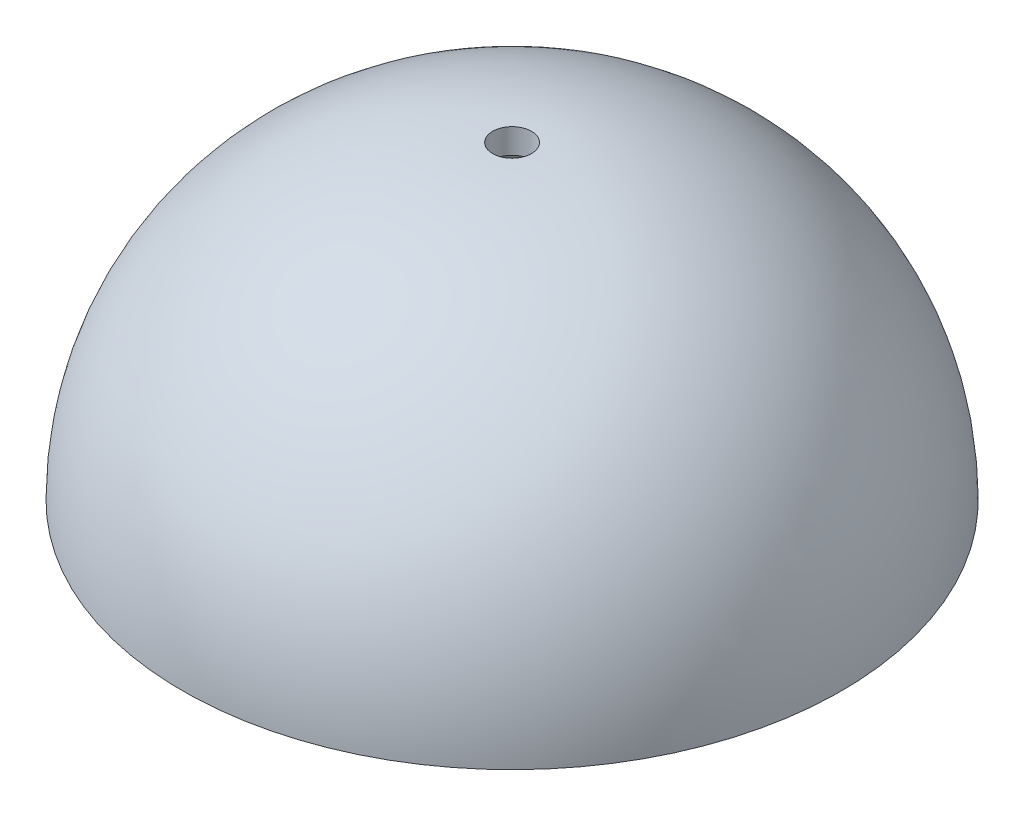
SolidWorks part; units mm, degrees
ref_plane "Front Plane" through (0, 0, 0) normal (0, 0, 1) x (1, 0, 0)
ref_plane "Top Plane" through (0, 0, 0) normal (0, 1, 0) x (1, 0, 0)
ref_plane "Right Plane" through (0, 0, 0) normal (1, 0, 0) x (0, 0, -1)
sketch "Sketch1" plane through (0, 0, 0) normal (0, 0, 1) x (1, 0, 0)
  line L0 (-0.7943, 0.007) -> (-0.7943, 2.2852) construction
  line L1 (-0.0006, 11.684) -> (-0.0006, 12.7)
  line L2 (11.6764, 0.007) -> (12.6924, 0.007)
  line L3 (-0.0006, 11.684) -> (-0.0006, 0.007) construction
  arc A0 (-0.0006, 12.7) -> (12.6924, 0.007) centre (-0.0006, 0.007) cw
  arc A1 (-0.0006, 11.684) -> (11.6764, 0.007) centre (-0.0006, 0.007) cw
  dimension "D2" = 1.016
  dimension "D1" = 0.7937
revolve "Revolve5" add sketch "Sketch1" angle 360 about L0
